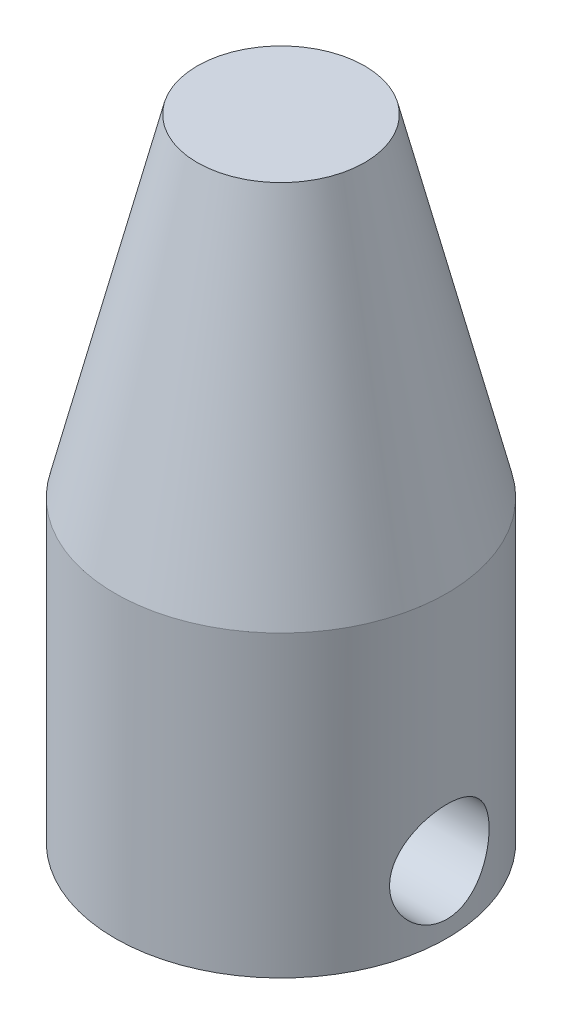
SolidWorks part; units mm, degrees
ref_plane "Front Plane" through (0, 0, 0) normal (0, 0, 1) x (1, 0, 0)
ref_plane "Top Plane" through (0, 0, 0) normal (0, 1, 0) x (1, 0, 0)
ref_plane "Right Plane" through (0, 0, 0) normal (1, 0, 0) x (0, 0, -1)
sketch "Sketch1" plane through (0, 0, 0) normal (0, 1, 0) x (1, 0, 0)
  circle A0 centre (0, 0) radius 5
  dimension "D1" = 10
extrude "body" add sketch "Sketch1" along normal blind 9
sketch "Sketch2" plane through (0, 0, 0) normal (1, 0, 0) x (0, 0, -1)
  circle A0 centre (0, 2) radius 1.5
  dimension "D1" = 2
  dimension "D2" = 3
extrude "pin insert" cut sketch "Sketch2" against normal through all and the other way through all
ref_plane "contact plane" through (0, 19, 0) normal (0, 1, 0) x (1, 0, 0)
sketch "head SA" plane through (0, 19, 0) normal (0, 1, 0) x (1, 0, 0)
  circle A0 centre (0, 0) radius 2.523
  dimension "D1" = 5.046
loft "cone" add profiles "head SA" section "head SA" section face at (0, 9, 5)
